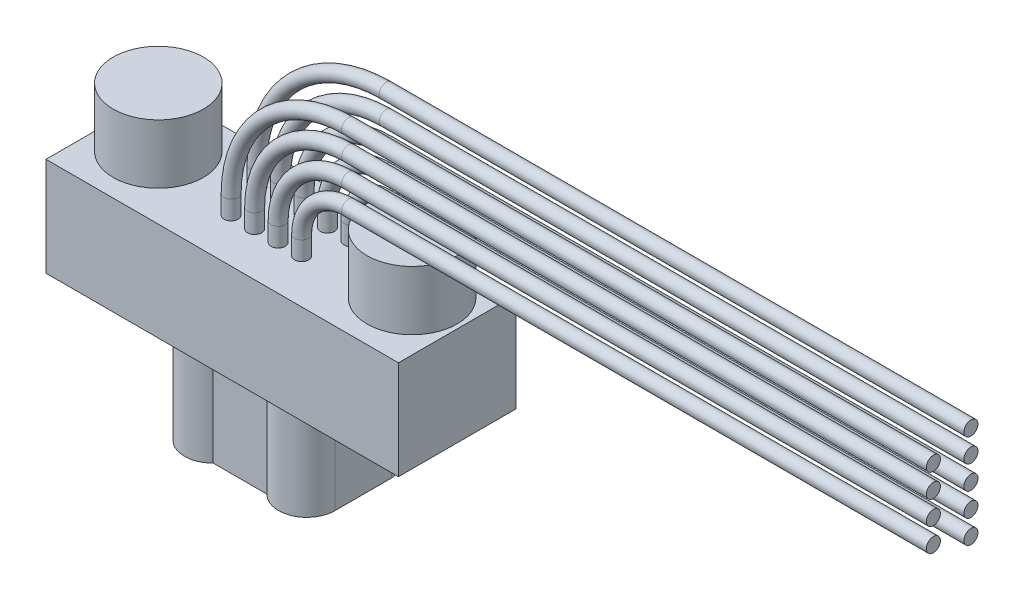
SolidWorks part; units mm, degrees
ref_plane "Front Plane" through (0, 0, 0) normal (0, 0, 1) x (1, 0, 0)
ref_plane "Top Plane" through (0, 0, 0) normal (0, 1, 0) x (1, 0, 0)
ref_plane "Right Plane" through (0, 0, 0) normal (1, 0, 0) x (0, 0, -1)
sketch "Sketch2" plane through (0, 0, 0) normal (0, 1, 0) x (1, 0, 0)
  line L5 (-4.7625, -1.7018) -> (4.7625, -1.7018)
  line L6 (4.7625, 1.4732) -> (4.7625, -1.7018)
  line L7 (-4.7625, 1.4732) -> (4.7625, 1.4732)
  line L8 (-4.7625, 1.4732) -> (-4.7625, -1.7018)
  point P4 (0, 1.4732)
  dimension "D1" = 1.4732
  dimension "D2" = 3.175
  dimension "D3" = 9.525
extrude "Boss-Extrude2" add sketch "Sketch2" along normal blind 2.667
sketch "Sketch7" plane through (0, 0, 0) normal (0, 1, 0) x (1, 0, 0)
  line L0 (-1.651, 1.2192) -> (1.651, 1.2192)
  line L1 (2.032, 0.8382) -> (2.032, -0.6858)
  line L2 (0.7258, -1.2192) -> (-0.7258, -1.2192)
  line L3 (0, -1.8912) -> (0, -4.5956) construction
  line L5 (-2.032, 0.8382) -> (-2.032, -0.6858)
  arc A0 (2.032, -0.6858) -> (0.7258, -1.2192) centre (1.27, -0.6858) cw
  arc A1 (1.651, 1.2192) -> (2.032, 0.8382) centre (1.651, 0.8382) cw
  arc A2 (-1.651, 1.2192) -> (-2.032, 0.8382) centre (-1.651, 0.8382) ccw
  arc A3 (-2.032, -0.6858) -> (-0.7258, -1.2192) centre (-1.27, -0.6858) ccw
  dimension "D1" = 0.381
  dimension "D6" = 0.762
  dimension "D2" = 4.064
  dimension "D3" = 1.2192
  dimension "D4" = 2.4384
  dimension "D5" = 2.667
sketch "Sketch4" plane through (0, 0, 0) normal (0, 1, 0) x (1, 0, 0)
  circle A0 centre (0.9525, -0.508) radius 0.1905
  circle A1 centre (0.3175, -0.508) radius 0.1905
  circle A2 centre (-0.3175, -0.508) radius 0.1905
  circle A3 centre (-0.9525, -0.508) radius 0.1905
  circle A4 centre (1.27, 0.508) radius 0.1905
  circle A5 centre (0.635, 0.508) radius 0.1905
  circle A6 centre (0, 0.508) radius 0.1905
  circle A7 centre (-0.635, 0.508) radius 0.1905
  circle A8 centre (-1.27, 0.508) radius 0.1905
  dimension "D1" = 0.635
  dimension "D2" = 0.635
  dimension "D3" = 0.635
  dimension "D4" = 0.381
  dimension "D7" = 0.508
  dimension "D8" = 0.635
  dimension "D9" = 0.635
  dimension "D10" = 0.635
  dimension "D11" = 0.635
  dimension "D5" = 0.508
  dimension "D6" = 0.3175
sketch "Sketch3" plane through (0, 0, 0) normal (0, 0, 1) x (1, 0, 0)
  line L0 (0.9525, 0) -> (0.9525, 3.175)
  line L2 (2.2225, 4.445) -> (18.0251, 4.445)
  arc A0 (0.9525, 3.175) -> (2.2225, 4.445) centre (2.2225, 3.175) cw
  dimension "D1" = 1.27
  dimension "D2" = 3.175
extrude "Boss-Extrude3" add sketch "Sketch7" against normal blind 2.667
sweep "Sweep1" add profiles "Sketch4" path "Sketch3"
sketch "Sketch8" plane through (0, 2.667, 0) normal (0, 1, 0) x (1, 0, 0)
  circle A0 centre (3.429, 0) radius 1.2192
  circle A1 centre (-3.429, 0) radius 1.2192
  dimension "D1" = 6.858
  dimension "D2" = 2.4384
  dimension "D3" = 3.429
extrude "Boss-Extrude4" add sketch "Sketch8" along normal blind 1.6002
